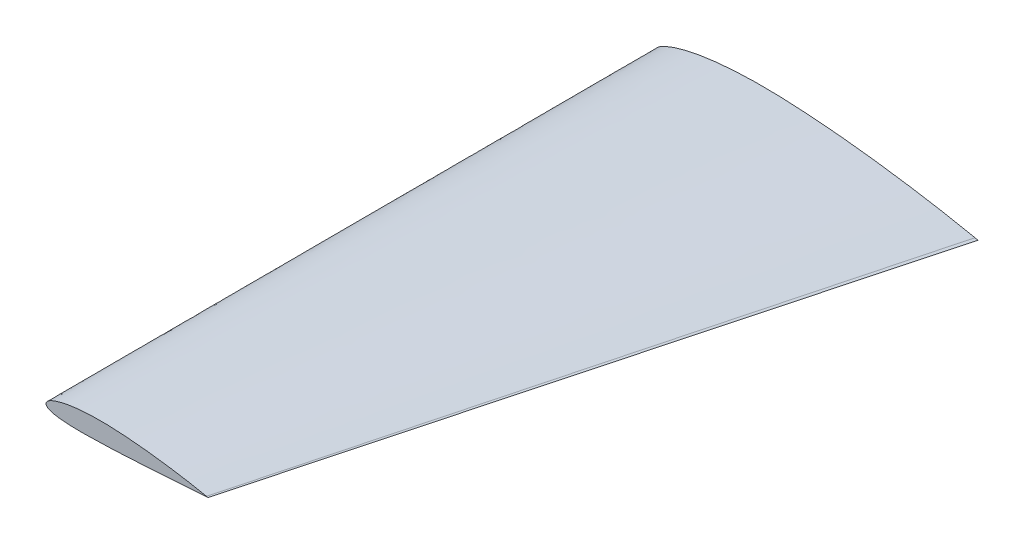
SolidWorks part; units mm, degrees
ref_plane "Front Plane" through (0, 0, 0) normal (0, 0, 1) x (1, 0, 0)
ref_plane "Top Plane" through (0, 0, 0) normal (0, 1, 0) x (1, 0, 0)
ref_plane "Right Plane" through (0, 0, 0) normal (1, 0, 0) x (0, 0, -1)
sketch "Sketch1" plane through (0, 0, 0) normal (0, 0, 1) x (1, 0, 0)
  line L0 (335.2297, -0.4358) -> (338.3936, -0.2125)
  line L1 (338.3936, -0.2125) -> (335.2297, 0.4358)
  spline S1 degree 3 poles (335.2297, 0.4358) (329.6456, 1.58) (318.4922, 3.8655) (296.1661, 8.0517) (268.2435, 12.6901) (234.7141, 17.4906) (201.1903, 21.4941) (167.652, 24.4255) (134.1213, 26.4106) (106.1456, 26.7466) (83.7872, 25.821) (67.0046, 24.4647) (50.2008, 22.3169) (36.2159, 19.6721) (25.0668, 16.6799) (16.6143, 13.9595) (9.4529, 10.7898) (3.2755, 6.947) (-2.1114, 0.3013) (3.4842, -5.5401) (9.546, -8.2044) (16.6759, -10.2281) (25.1006, -11.6792) (36.2943, -12.9175) (50.2667, -13.8706) (67.044, -14.2527) (83.8093, -14.1995) (106.16, -13.7061) (134.101, -12.8183) (167.626, -11.2734) (201.1414, -9.2653) (234.6624, -7.178) (268.1892, -5.0653) (296.1189, -3.1194) (318.4696, -1.6186) (329.6428, -0.8301) (335.2297, -0.4358) knots 0 0 0 0 0.025012 0.049959 0.099673 0.149206 0.198581 0.247805 0.296917 0.345953 0.370492 0.395091 0.419815 0.444799 0.45749 0.470406 0.483879 0.491264 0.503459 0.513609 0.520451 0.533235 0.545691 0.558032 0.582609 0.607135 0.631652 0.656174 0.705234 0.75432 0.803437 0.852566 0.901701 0.950849 0.975423 1 1 1 1
ref_plane "Plane1" through (0, 0, 635) normal (0, 0, -1) x (-1, 0, 0)
sketch "Sketch2" plane through (0, 0, 635) normal (0, 0, -1) x (-1, 0, 0)
  line L4 (-169.1968, -0.1063) -> (-167.6149, -0.2179)
  line L5 (-167.6149, 0.2179) -> (-169.1968, -0.1063)
  spline S2 degree 3 poles (-167.6149, -0.2179) (-164.8214, -0.415) (-159.2348, -0.8093) (-148.0595, -1.5597) (-134.0946, -2.5326) (-117.3312, -3.589) (-100.5707, -4.6326) (-83.813, -5.6367) (-67.0505, -6.4092) (-53.08, -6.8531) (-41.9046, -7.0997) (-33.522, -7.1264) (-25.1333, -6.9353) (-18.1471, -6.4587) (-12.5503, -5.8396) (-8.3379, -5.1141) (-4.773, -4.1022) (-1.7421, -2.7701) (1.0557, 0.1506) (-1.6378, 3.4735) (-4.7264, 5.3949) (-8.3071, 6.9797) (-12.5334, 8.3399) (-18.1079, 9.8361) (-25.1004, 11.1585) (-33.5023, 12.2324) (-41.8936, 12.9105) (-53.0728, 13.3733) (-67.0607, 13.2053) (-83.826, 12.2127) (-100.5952, 10.747) (-117.3571, 8.7453) (-134.1217, 6.345) (-148.0831, 4.0259) (-159.2461, 1.9328) (-164.8228, 0.79) (-167.6149, 0.2179) knots 0 0 0 0 0.024577 0.049151 0.098299 0.147434 0.196563 0.24568 0.294766 0.343826 0.368348 0.392865 0.417391 0.441968 0.454309 0.466765 0.479549 0.486391 0.496541 0.508736 0.516121 0.529594 0.54251 0.555201 0.580185 0.604909 0.629508 0.654047 0.703083 0.752195 0.801419 0.850794 0.900327 0.950041 0.974988 1 1 1 1
loft "Loft1" add profiles "Sketch2", "Sketch1"
